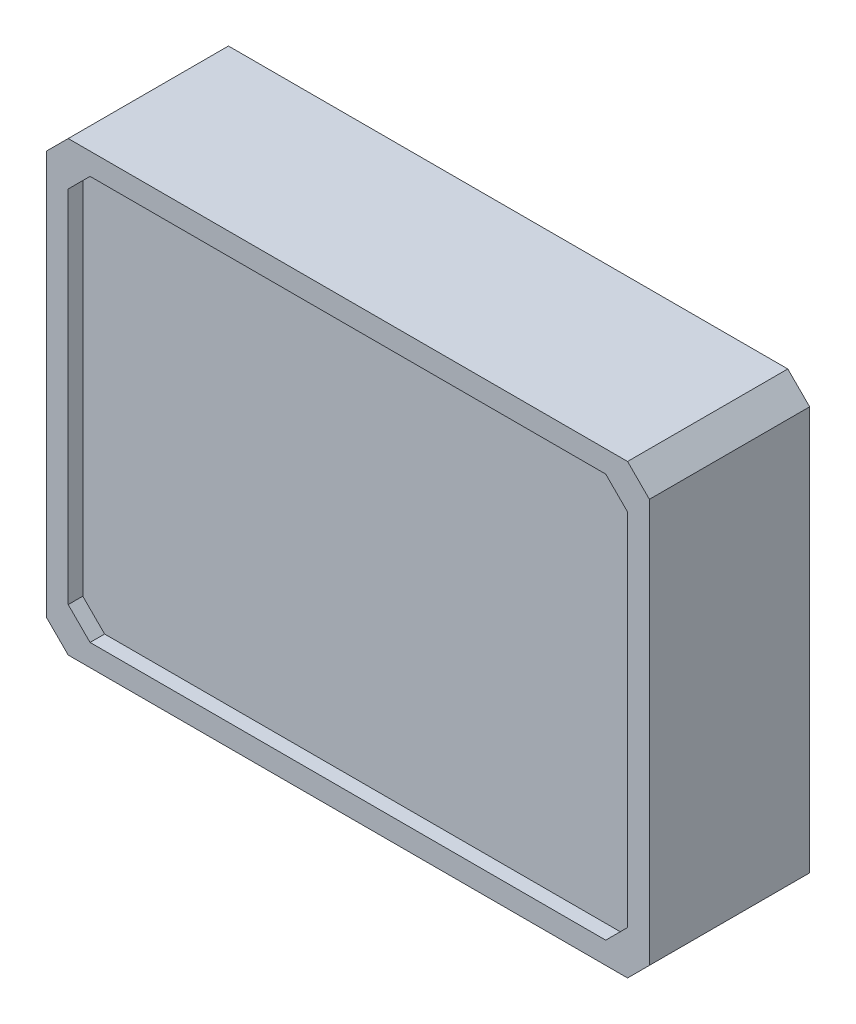
SolidWorks part; units mm, degrees
ref_plane "前视基准面" through (0, 0, 0) normal (0, 0, 1) x (1, 0, 0)
ref_plane "上视基准面" through (0, 0, 0) normal (0, 1, 0) x (1, 0, 0)
ref_plane "右视基准面" through (0, 0, 0) normal (1, 0, 0) x (0, 0, -1)
other "Configuration Table"
sketch "草图1" plane through (0, 0, 0) normal (0, 0, 1) x (1, 0, 0)
  line L0 (-38.4, -30.7095) -> (38.4, -30.7095)
  line L1 (38.4, -30.7095) -> (41.4, -27.7095)
  line L2 (41.4, -27.7095) -> (41.4, 27.7095)
  line L3 (41.4, 27.7095) -> (38.4, 30.7095)
  line L4 (38.4, 30.7095) -> (-38.4, 30.7095)
  line L5 (-38.4, 30.7095) -> (-41.4, 27.7095)
  line L6 (-41.4, 27.7095) -> (-41.4, -27.7095)
  line L7 (-41.4, -27.7095) -> (-38.4, -30.7095)
  dimension "D1" = 38.4
  dimension "D2" = 41.4
  dimension "D3" = 38.4
  dimension "D4" = 27.7095
  dimension "D5" = 30.7095
  dimension "D6" = 27.7095
extrude "Support_plane_exactly_20mm_above_table" add sketch "草图1" along normal blind 20
sketch "草图2" plane through (0, 0, 0) normal (0, 0, 1) x (1, 0, 0)
  line L0 (-38.4, -30.7095) -> (38.4, -30.7095)
  line L1 (38.4, -30.7095) -> (41.4, -27.7095)
  line L2 (41.4, -27.7095) -> (41.4, 27.7095)
  line L3 (41.4, 27.7095) -> (38.4, 30.7095)
  line L4 (38.4, 30.7095) -> (-38.4, 30.7095)
  line L5 (-38.4, 30.7095) -> (-41.4, 27.7095)
  line L6 (-41.4, 27.7095) -> (-41.4, -27.7095)
  line L7 (-41.4, -27.7095) -> (-38.4, -30.7095)
  line L8 (-35.4, -27.7095) -> (35.4, -27.7095)
  line L9 (35.4, -27.7095) -> (38.4, -24.7095)
  line L10 (38.4, -24.7095) -> (38.4, 24.7095)
  line L11 (38.4, 24.7095) -> (35.4, 27.7095)
  line L12 (35.4, 27.7095) -> (-35.4, 27.7095)
  line L13 (-35.4, 27.7095) -> (-38.4, 24.7095)
  line L14 (-38.4, 24.7095) -> (-38.4, -24.7095)
  line L15 (-38.4, -24.7095) -> (-35.4, -27.7095)
  dimension "D1" = 35.4
  dimension "D2" = 38.4
  dimension "D3" = 41.4
  dimension "D4" = 35.4
  dimension "D5" = 24.7095
  dimension "D6" = 27.7095
  dimension "D7" = 24.7095
extrude "Low_locating_lip_0p4mm_clearance_each_side" add sketch "草图2" along normal blind 2 from offset 20
